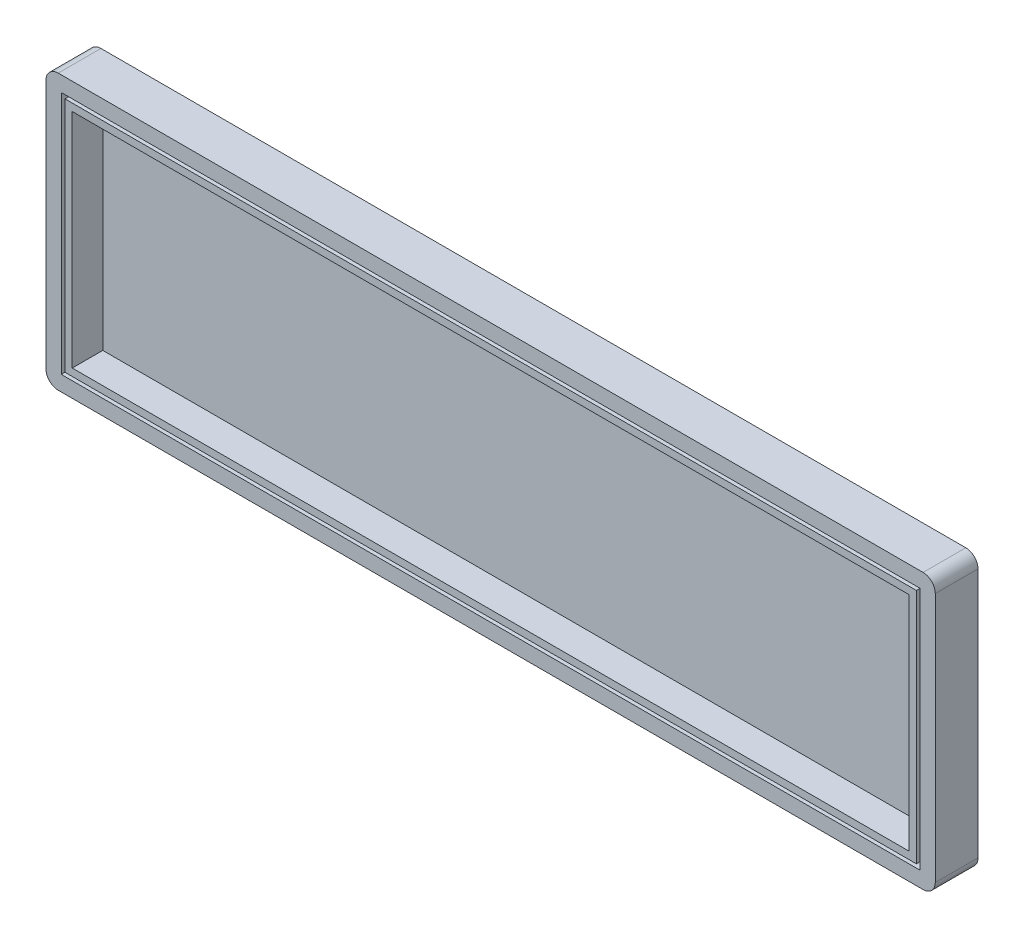
SolidWorks part; units mm, degrees
ref_plane "Front Plane" through (0, 0, 0) normal (0, 0, 1) x (1, 0, 0)
ref_plane "Top Plane" through (0, 0, 0) normal (0, 1, 0) x (1, 0, 0)
ref_plane "Right Plane" through (0, 0, 0) normal (1, 0, 0) x (0, 0, -1)
sketch "Sketch1" plane through (0, 0, 0) normal (0, 0, 1) x (1, 0, 0)
  line L1 (0, 0) -> (145.7, 0)
  line L2 (0, 0) -> (0, 45)
  line L3 (0, 45) -> (145.7, 45)
  line L4 (145.7, 0) -> (145.7, 45)
  dimension "D1" = 45
  dimension "D2" = 145.7
extrude "Boss-Extrude1" add sketch "Sketch1" along normal blind 2
sketch "Sketch17" plane through (0, 0, 2) normal (0, 0, 1) x (1, 0, 0)
  line L1 (0, 45) -> (145.7, 45)
  line L2 (0, 45) -> (0, 0)
  line L3 (0, 0) -> (145.7, 0)
  line L4 (145.7, 45) -> (145.7, 0)
  line L5 (143.2, 2.5) -> (2.5, 2.5)
  line L6 (143.2, 2.5) -> (143.2, 42.5)
  line L7 (143.2, 42.5) -> (2.5, 42.5)
  line L8 (2.5, 2.5) -> (2.5, 42.5)
  line L9 (3.1, 41.9) -> (142.6, 41.9)
  line L10 (3.1, 41.9) -> (3.1, 3.1)
  line L11 (3.1, 3.1) -> (142.6, 3.1)
  line L12 (142.6, 41.9) -> (142.6, 3.1)
  line L13 (4.3, 40.7) -> (141.4, 40.7)
  line L14 (4.3, 40.7) -> (4.3, 4.3)
  line L15 (4.3, 4.3) -> (141.4, 4.3)
  line L16 (141.4, 40.7) -> (141.4, 4.3)
  point P18 (143.2, 22.5)
  point P19 (145.7, 22.5)
  point P20 (142.6, 22.5)
  point P21 (141.4, 22.5)
  point P22 (72.85, 42.5)
  point P23 (72.85, 45)
  point P24 (72.85, 41.9)
  point P25 (72.85, 40.7)
  dimension "D1" = 0.6
  dimension "D2" = 0.6
  dimension "D3" = 2.5
  dimension "D4" = 2.5
  dimension "D5" = 1.2
  dimension "D6" = 1.2
extrude "Boss-Extrude10" add sketch "Sketch17" along normal blind 5 contours L4 L1 L2 L3 L5 L8 L7 L6 | L12 L9 L10 L11 L13 L16 L15 L14
fillet "Fillet2" radius 2 4 edges at (145.7, 45, 3.5) (145.7, 0, 3.5) (0, 45, 3.5) (0, 0, 3.5)
